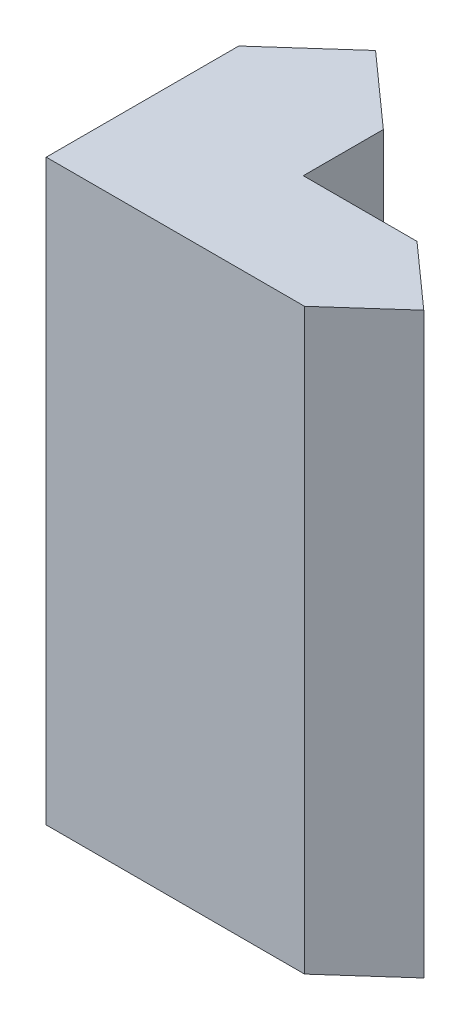
SolidWorks part; units mm, degrees
ref_plane "前视基准面" through (0, 0, 0) normal (0, 0, 1) x (1, 0, 0)
ref_plane "上视基准面" through (0, 0, 0) normal (0, 1, 0) x (1, 0, 0)
ref_plane "右视基准面" through (0, 0, 0) normal (1, 0, 0) x (0, 0, -1)
sketch "草图1" plane through (0, 0, 0) normal (0, 1, 0) x (1, 0, 0)
  line L0 (-18.4063, 0) -> (61.9852, 0)
  line L1 (61.9852, 0) -> (81.5937, 17.5)
  line L2 (81.5937, 17.5) -> (61.9852, 35)
  line L3 (61.9852, 35) -> (26.5937, 35)
  line L4 (26.5937, 35) -> (26.5937, 59.9194)
  line L5 (26.5937, 59.9194) -> (4.0937, 80)
  line L6 (4.0937, 80) -> (-18.4063, 59.9194)
  line L7 (-18.4063, 59.9194) -> (-18.4063, 0)
  dimension "D1" = 100
  dimension "D2" = 80
  dimension "D3" = 35
  dimension "D4" = 17.5
  dimension "D5" = 45
  dimension "D6" = 22.5
extrude "凸台-拉伸1" add sketch "草图1" along normal blind 180
sketch "草图4" plane through (26.5937, 0, 0) normal (1, 0, 0) x (0, 0, -1)
  line L6 (35, 0) -> (150.6885, 0)
  line L7 (35, 0) -> (35, 90)
  line L8 (35, 90) -> (150.6885, 90)
  line L9 (150.6885, 0) -> (150.6885, 90)
  dimension "D1" = 90
extrude "切除-拉伸1" cut sketch "草图4" against normal blind 200
